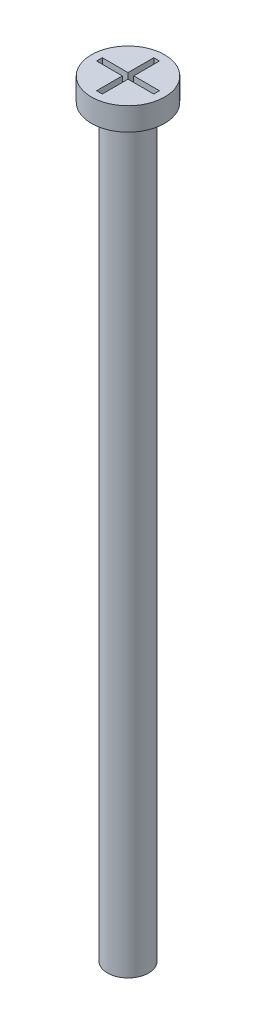
SolidWorks part; units mm, degrees
ref_plane "Front" through (0, 0, 0) normal (0, 0, 1) x (1, 0, 0)
ref_plane "Top" through (0, 0, 0) normal (0, 1, 0) x (1, 0, 0)
ref_plane "Right" through (0, 0, 0) normal (1, 0, 0) x (0, 0, -1)
sketch "Sketch1" plane through (0, 0, 0) normal (0, 0, 1) x (1, 0, 0)
  line L0 (0, 0) -> (1.6, 0)
  line L1 (1.6, 0) -> (1.6, -1)
  line L2 (1.6, -1) -> (0.9, -1)
  line L3 (0.9, -1) -> (0.9, -33.5)
  line L4 (0.9, -33.5) -> (0, -33.5)
  line L5 (0, -33.5) -> (0, 0)
  dimension "D1" = 0.9
  dimension "D2" = 1.6
  dimension "D3" = 1
  dimension "D4" = 32.5
revolve "Revolve1" add sketch "Sketch1" angle 360 about L5
sketch "Sketch2" plane through (0, 0, 0) normal (0, 1, 0) x (1, 0, 0)
  line L1 (-1.25, -0.125) -> (1.25, -0.125)
  line L2 (-1.25, -0.125) -> (-1.25, 0.125)
  line L3 (-1.25, 0.125) -> (1.25, 0.125)
  line L4 (1.25, -0.125) -> (1.25, 0.125)
  line L5 (-1.25, -0.125) -> (1.25, 0.125) construction
  line L6 (-1.25, 0.125) -> (1.25, -0.125) construction
  line L7 (-0.125, -1.25) -> (0.125, -1.25)
  line L8 (-0.125, -1.25) -> (-0.125, 1.25)
  line L9 (-0.125, 1.25) -> (0.125, 1.25)
  line L10 (0.125, -1.25) -> (0.125, 1.25)
  line L11 (-0.125, -1.25) -> (0.125, 1.25) construction
  line L12 (-0.125, 1.25) -> (0.125, -1.25) construction
  point P0 (0, 0)
  point P6 (0, 0)
  dimension "D1" = 0.25
  dimension "D2" = 2.5
extrude "Cut-Extrude1" cut sketch "Sketch2" against normal blind 0.5 contours L7 L10 L1 L8 | L1 L8 L3 L2 | L3 L10 L9 L8 | L10 L1 L4 L3 | L1 L10 L3 L8
